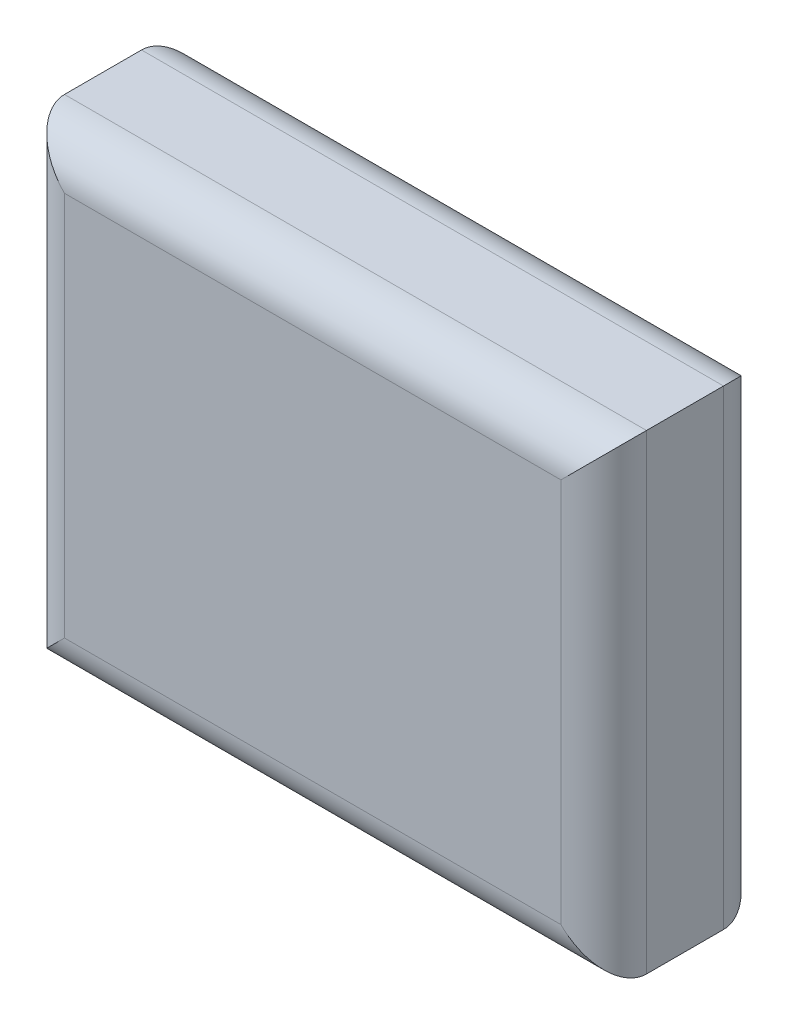
SolidWorks part; units mm, degrees
ref_plane "前视基准面" through (0, 0, 0) normal (0, 0, 1) x (1, 0, 0)
ref_plane "上视基准面" through (0, 0, 0) normal (0, 1, 0) x (1, 0, 0)
ref_plane "右视基准面" through (0, 0, 0) normal (1, 0, 0) x (0, 0, -1)
other "Configuration Table"
sketch "草图1" plane through (0, 0, 0) normal (0, 0, 1) x (1, 0, 0)
  line L1 (34, -27.5) -> (-34, -27.5)
  line L2 (34, -27.5) -> (34, 27.5)
  line L3 (34, 27.5) -> (-34, 27.5)
  line L4 (-34, -27.5) -> (-34, 27.5)
  line L5 (34, -27.5) -> (-34, 27.5) construction
  line L6 (34, 27.5) -> (-34, -27.5) construction
  point P0 (0, 0)
  dimension "D1" = 68
  dimension "D2" = 55
extrude "凸台-拉伸1" add sketch "草图1" along normal blind 19
fillet "圆角1" radius 5 8 edges at (0, -27.5, 0) (34, 0, 0) (0, 27.5, 0) (-34, 0, 0) (0, 27.5, 19) (-34, 0, 19) (0, -27.5, 19) (34, 0, 19)
